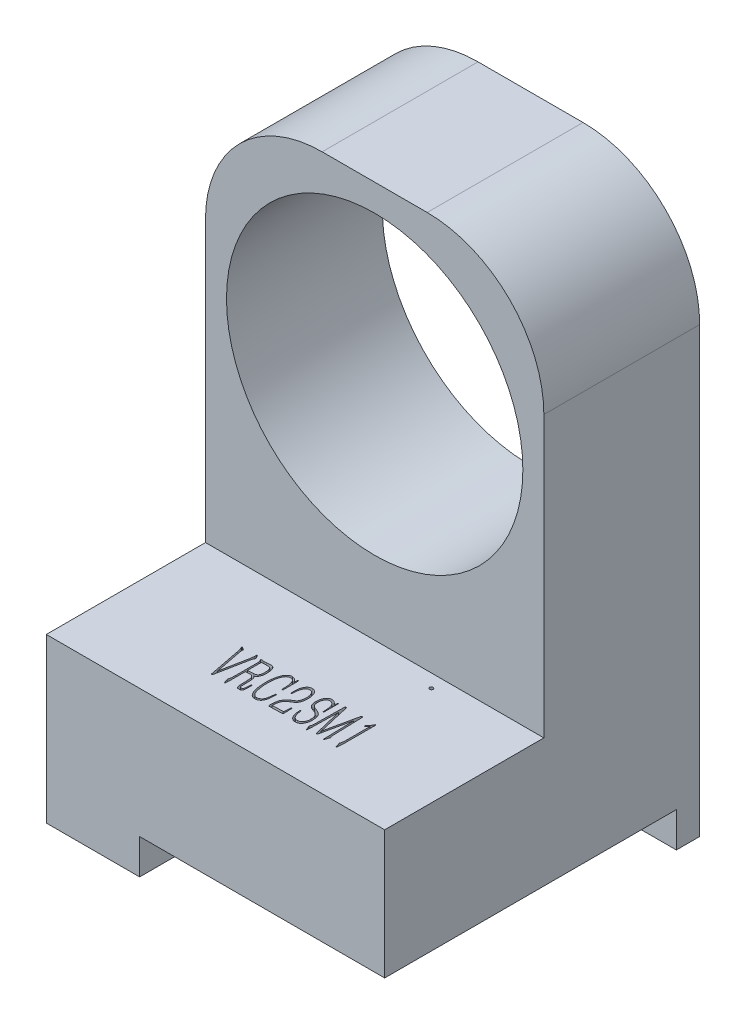
SolidWorks part; units mm, degrees
material "6061 合金"
ref_plane "前视基准面" through (0, 0, 0) normal (0, 0, 1) x (1, 0, 0)
ref_plane "上视基准面" through (0, 0, 0) normal (0, 1, 0) x (1, 0, 0)
ref_plane "右视基准面" through (0, 0, 0) normal (1, 0, 0) x (0, 0, -1)
sketch "草图1" plane through (0, 0, 0) normal (0, 1, 0) x (1, 0, 0)
  line L1 (-14.5, 14.5) -> (14.5, 14.5)
  line L2 (-14.5, 14.5) -> (-14.5, -14.5)
  line L3 (-14.5, -14.5) -> (14.5, -14.5)
  line L4 (14.5, 14.5) -> (14.5, -14.5)
  line L5 (-14.5, 14.5) -> (14.5, -14.5) construction
  line L6 (-14.5, -14.5) -> (14.5, 14.5) construction
  point P0 (0, 0)
  dimension "D1" = 29
  dimension "D2" = 29
extrude "凸台-拉伸1" add sketch "草图1" along normal blind 5
sketch "草图2" plane through (0, 0, 0) normal (0, -1, 0) x (1, 0, 0)
  line L1 (-12.5, 12.5) -> (12.5, 12.5)
  line L2 (-12.5, 12.5) -> (-12.5, -12.5)
  line L3 (-12.5, -12.5) -> (12.5, -12.5)
  line L4 (12.5, 12.5) -> (12.5, -12.5)
  line L5 (-12.5, 12.5) -> (12.5, -12.5) construction
  line L6 (-12.5, -12.5) -> (12.5, 12.5) construction
  point P0 (0, 0)
  dimension "D1" = 25
  dimension "D2" = 25
extrude "切除-拉伸1" cut sketch "草图2" against normal blind 3
sketch "草图3" plane through (0, 5, 0) normal (0, 1, 0) x (1, 0, 0)
  line L0 (0, 0) -> (-6, 0) construction
  line L1 (-16.5, 0) -> (16.5, 0) construction
  line L2 (-6, 0) -> (-6, 7.1924) construction
  dimension "D1" = 6
sketch "草图4" plane through (0, 5, 0) normal (0, 1, 0) x (1, 0, 0)
  line L0 (-14.5, -14.5) -> (14.5, -14.5) construction
  line L1 (-20.5, 14.5) -> (8.5, 14.5)
  line L2 (-20.5, 14.5) -> (-20.5, -14.5)
  line L3 (-20.5, -14.5) -> (8.5, -14.5)
  line L4 (8.5, 14.5) -> (8.5, -14.5)
  line L5 (-20.5, 14.5) -> (8.5, -14.5) construction
  line L6 (-20.5, -14.5) -> (8.5, 14.5) construction
  point P0 (-6, 0)
  dimension "D1" = 29
extrude "凸台-拉伸2" add sketch "草图4" along normal blind 43
sketch "草图6" plane through (0, 3, 0) normal (0, -1, 0) x (1, 0, 0)
  circle A0 centre (0, 0) radius 1.4439
hole_wizard "M4 螺纹孔1" positions "3D草图2" profile "草图7" tap size "M4" standard "GB"
sketch3d "3D草图2"
  point P0 (0, 0, 0)
  point P3 (0, 3, 0)
sketch "草图7" plane through (0, 3, 0) normal (1, 0, 0) x (0, 0, -1)
  line L0 (0, 0) -> (0, 11.0914)
  line L1 (0, 11.0914) -> (1.65, 10.1)
  line L2 (1.65, 10.1) -> (1.65, 0)
  line L5 (1.65, 0) -> (0, 0)
  line L10 (0, 11.0914) -> (-1.65, 10.1) construction
  line L11 (0, -6.35) -> (0, 107.95) construction
  dimension "螺纹孔钻头直径" = 3.3
  dimension "螺纹孔钻头深度" = 10.1
  dimension "导头角度" = 118
cosmetic thread "孔螺蚊线2" parameters "D1"=8, "D2"=4
sketch "草图8" plane through (0, 0, 14.5) normal (0, 0, 1) x (1, 0, 0)
  line L0 (-6, 48) -> (-6, 33) construction
  line L1 (-20.5, 48) -> (8.5, 48) construction
  line L2 (12.5, 3) -> (-12.5, 3) construction
  dimension "D1" = 30
hole_wizard "M27 螺纹孔1" positions "3D草图3" profile "草图9" tap size "M27" standard "GB" end condition through all
sketch3d "3D草图3"
  point P0 (-6, 33, 14.5)
sketch "草图9" plane through (-6, 33, 14.5) normal (1, 0, 0) x (0, -1, 0)
  line L0 (0, 0) -> (0, 29)
  line L1 (0, 29) -> (12.7, 29)
  line L2 (12.7, 29) -> (12.7, 0)
  line L5 (12.7, 0) -> (0, 0)
  line L11 (0, -6.35) -> (0, 107.95) construction
  dimension "通孔螺纹孔钻头直径" = 25.4
  dimension "通孔螺纹孔钻头深度" = 29
cosmetic thread "孔螺蚊线3" parameters "D2"=27
sketch "草图10" plane through (0, 0, 14.5) normal (0, 0, 1) x (1, 0, 0)
  circle A0 centre (-6, 33) radius 18
extrude "切除-拉伸2" cut sketch "草图10" against normal up to surface (15.643 mm away)
sketch "草图11" plane through (0, 0, 0) normal (0, -1, 0) x (-1, 0, 0)
  circle A0 centre (12.5, 12.5) radius 1
extrude "切除-拉伸3" cut sketch "草图11" against normal up to surface (3 mm away) up to face at (0, 3, -1.65)
sketch "草图12" plane through (0, 0, 14.5) normal (0, 0, 1) x (1, 0, 0)
  line L2 (-20.5, 48) -> (-20.5, 43.6654)
  line L3 (-15.9499, 48) -> (-20.5, 48)
  line L4 (-20.5, 48) -> (-20.5, 43.6654)
  line L5 (-15.9499, 48) -> (-20.5, 48)
  line L6 (8.5, 48) -> (3.9499, 48)
  line L7 (8.5, 43.6654) -> (8.5, 48)
  line L8 (8.5, 48) -> (3.9499, 48)
  line L9 (8.5, 43.6654) -> (8.5, 48)
  arc A1 (-15.9499, 48) -> (-20.5, 43.6654) centre (-6, 33) ccw
  arc A2 (-15.9499, 48) -> (-20.5, 43.6654) centre (-6, 33) ccw
  arc A3 (8.5, 43.6654) -> (3.9499, 48) centre (-6, 33) ccw
  arc A4 (8.5, 43.6654) -> (3.9499, 48) centre (-6, 33) ccw
  dimension "D1" = 0
  dimension "D2" = 0
extrude "切除-拉伸4" cut sketch "草图12" against normal up to surface (15.643 mm away) up to face at (-18.7, 33, -1.143)
sketch "草图13" plane through (-14.5, 0, 0) normal (-1, 0, 0) x (0, 0, 1)
  line L4 (-14.5, 0) -> (14.5, 0)
  line L5 (14.5, 0) -> (14.5, 5)
  line L6 (14.5, 5) -> (-14.5, 5)
  line L7 (-14.5, 5) -> (-14.5, 0)
  line L8 (-14.5, 0) -> (14.5, 0)
  line L9 (14.5, 0) -> (14.5, 5)
  line L10 (14.5, 5) -> (-14.5, 5)
  line L11 (-14.5, 5) -> (-14.5, 0)
  dimension "D1" = 0
extrude "凸台-拉伸3" add sketch "草图13" along normal up to surface (6 mm away) up to face at (-20.5, 25.1115, -0.381)
sketch "草图14" plane through (0, 5, 0) normal (0, 1, 0) x (1, 0, 0)
  line L4 (8.5, 14.5) -> (8.5, -14.5)
  line L5 (8.5, -14.5) -> (14.5, -14.5)
  line L6 (14.5, -14.5) -> (14.5, 14.5)
  line L7 (14.5, 14.5) -> (8.5, 14.5)
  line L8 (8.5, 14.5) -> (8.5, -14.5)
  line L9 (8.5, -14.5) -> (14.5, -14.5)
  line L10 (14.5, -14.5) -> (14.5, 14.5)
  line L11 (14.5, 14.5) -> (8.5, 14.5)
  dimension "D1" = 0
extrude "切除-拉伸5" cut sketch "草图14" against normal through all
sketch "草图15" plane through (0, 0, 0) normal (0, -1, 0) x (1, 0, 0)
  line L1 (8.5, 12.5) -> (-20.5, 12.5)
  line L2 (8.5, 12.5) -> (8.5, 14.5)
  line L3 (8.5, 14.5) -> (-20.5, 14.5)
  line L4 (-20.5, 12.5) -> (-20.5, 14.5)
extrude "切除-拉伸6" cut sketch "草图15" against normal through all
fillet "圆角1" radius 10 2 edges at (8.5, 48, -7.8215) (-20.5, 48, -7.8215)
sketch "草图16" plane through (0, 0, 12.5) normal (0, 0, 1) x (1, 0, 0)
  line L0 (-20.5, 22.3346) -> (-20.5, 14)
  line L1 (-20.5, 22.3346) -> (-20.5, 0) construction
  line L2 (-20.5, 14) -> (8.5, 14)
  line L3 (8.5, 22.3346) -> (8.5, 3) construction
  line L4 (8.5, 14) -> (8.5, 22.3346)
  line L5 (-20.5, 0) -> (-12.5, 0) construction
  arc A0 (-20.5, 22.3346) -> (8.5, 22.3346) centre (-6, 33) ccw construction
  arc A1 (-20.5, 22.3346) -> (8.5, 22.3346) centre (-6, 33) ccw
  dimension "D1" = 14
extrude "切除-拉伸7" cut sketch "草图16" against normal up to surface (13.643 mm away) up to face at (-18.7, 33, -1.143)
sketch "草图17" plane through (0, 14, 0) normal (0, 1, 0) x (1, 0, 0)
  text T0 "VRC2SM1"
extrude "切除-拉伸8" cut sketch "草图17" against normal blind 0.5
